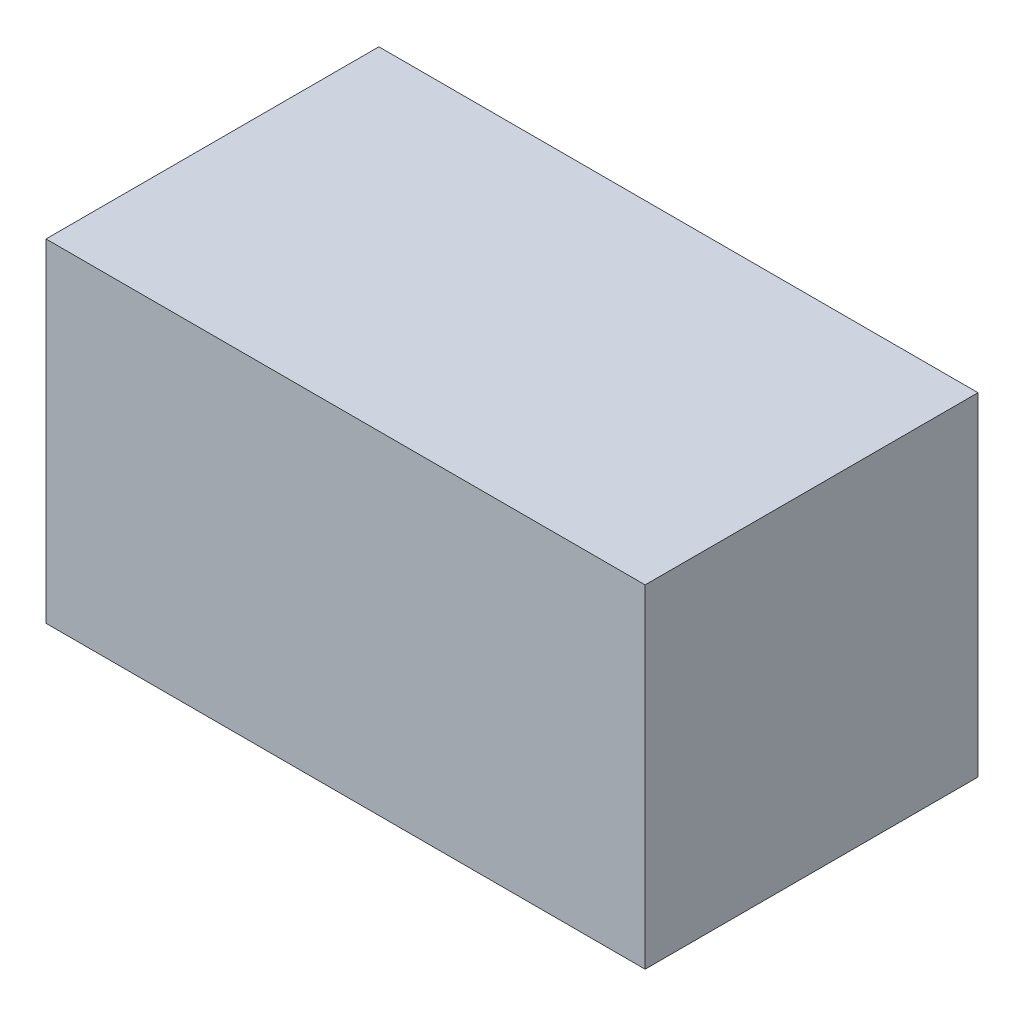
SolidWorks part; units mm, degrees
ref_plane "前视基准面" through (0, 0, 0) normal (0, 0, 1) x (1, 0, 0)
ref_plane "上视基准面" through (0, 0, 0) normal (0, 1, 0) x (1, 0, 0)
ref_plane "右视基准面" through (0, 0, 0) normal (1, 0, 0) x (0, 0, -1)
sketch "草图1" plane through (0, 0, 0) normal (0, 1, 0) x (1, 0, 0)
  line L1 (-97.9499, 42.8246) -> (82.0501, 42.8246)
  line L2 (-97.9499, 42.8246) -> (-97.9499, -57.1754)
  line L3 (-97.9499, -57.1754) -> (82.0501, -57.1754)
  line L4 (82.0501, 42.8246) -> (82.0501, -57.1754)
  dimension "D1" = 180
  dimension "D2" = 100
extrude "凸台-拉伸1" add sketch "草图1" along normal blind 100 contours L1 L4 L3 L2
